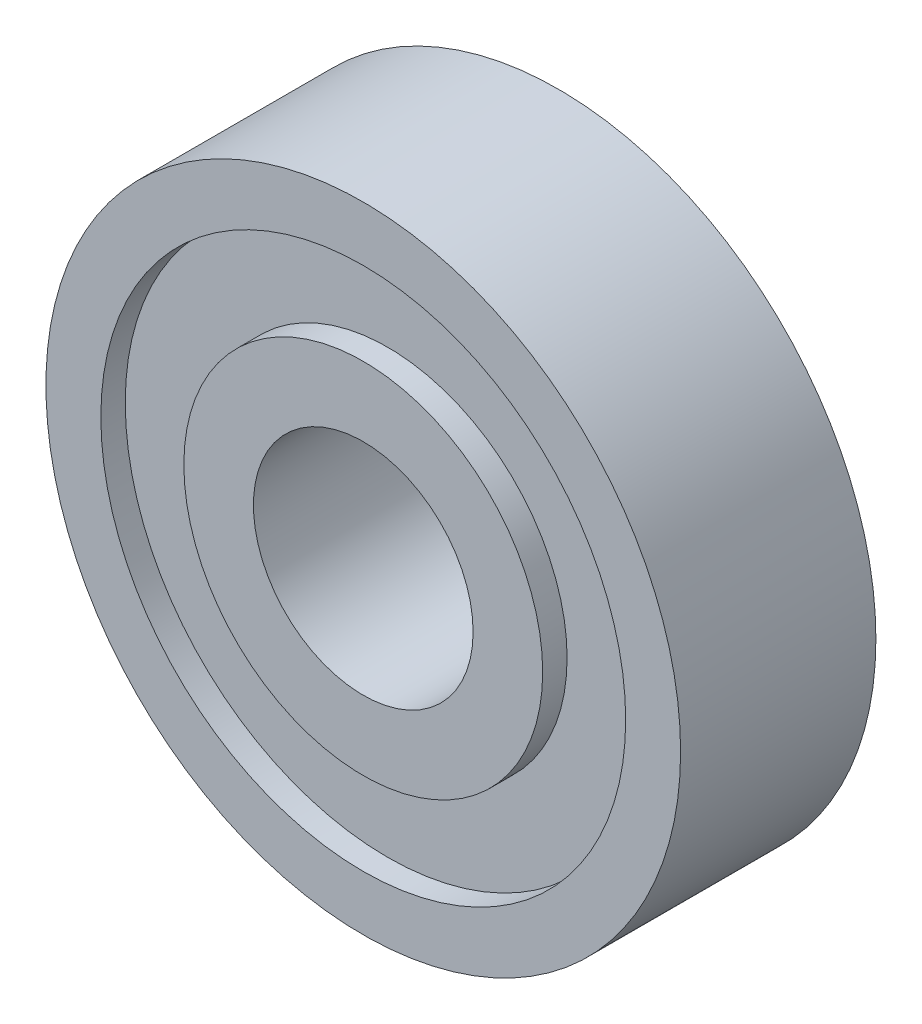
SolidWorks part; units mm, degrees
ref_plane "Спереди" through (0, 0, 0) normal (0, 0, 1) x (1, 0, 0)
ref_plane "Сверху" through (0, 0, 0) normal (0, 1, 0) x (1, 0, 0)
ref_plane "Справа" through (0, 0, 0) normal (1, 0, 0) x (0, 0, -1)
sketch "Эскиз1" plane through (0, 0, 0) normal (0, 0, 1) x (1, 0, 0)
  circle A0 centre (0, 0) radius 13
  circle A1 centre (0, 0) radius 4.5
  dimension "D1" = 26
  dimension "D2" = 9
extrude "Бобышка-Вытянуть1" add sketch "Эскиз1" along normal blind 8
sketch "Эскиз2" plane through (0, 0, 8) normal (0, 0, 1) x (1, 0, 0)
  circle A0 centre (0, 0) radius 7.35
  circle A3 centre (0, 0) radius 10.75
  dimension "D1" = 21.5
  dimension "D2" = 14.7
extrude "Вырез-Вытянуть1" cut sketch "Эскиз2" against normal blind 1
sketch "Эскиз3" plane through (0, 0, 0) normal (0, 0, -1) x (-1, 0, 0)
  circle A0 centre (0, 0) radius 7.35
  circle A3 centre (0, 0) radius 7.35 construction
  circle A4 centre (0, 0) radius 10.75
  circle A5 centre (0, 0) radius 10.75 construction
extrude "Вырез-Вытянуть2" cut sketch "Эскиз3" against normal blind 1
